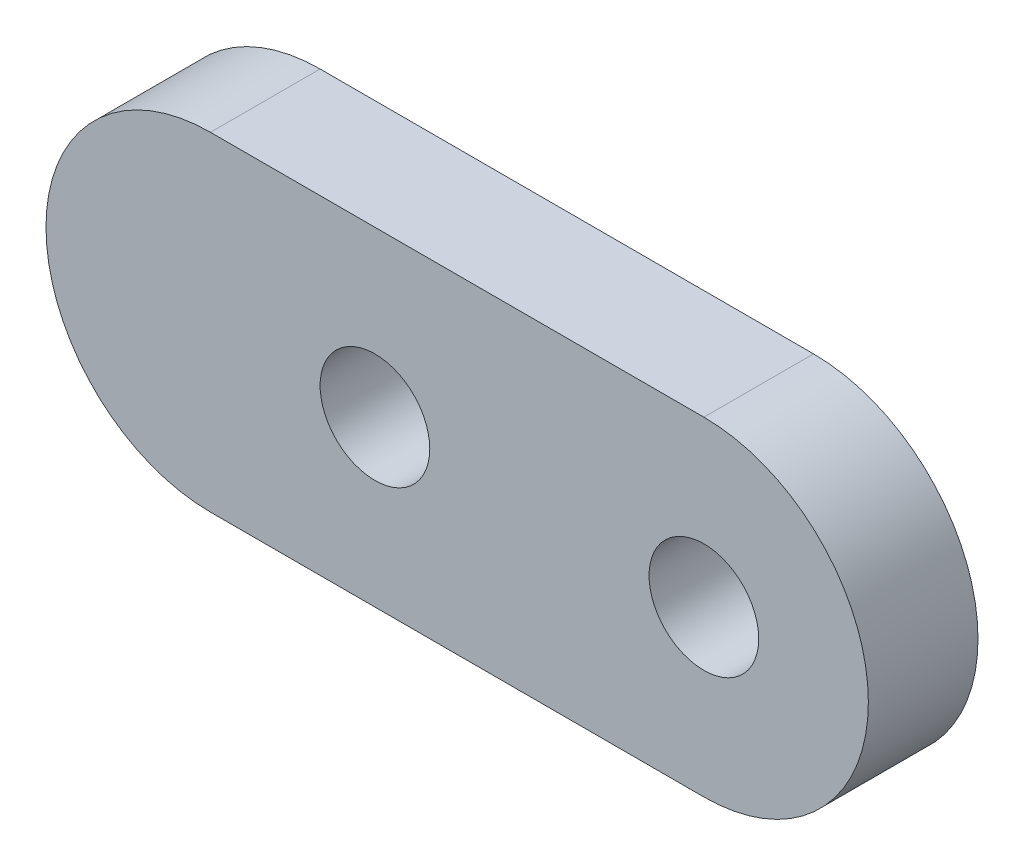
SolidWorks part; units mm, degrees
ref_plane "Alzado" through (0, 0, 0) normal (0, 0, 1) x (1, 0, 0)
ref_plane "Planta" through (0, 0, 0) normal (0, 1, 0) x (1, 0, 0)
ref_plane "Vista lateral" through (0, 0, 0) normal (1, 0, 0) x (0, 0, -1)
sketch "Model" plane through (0, 0, 0) normal (0, 0, 1) x (1, 0, 0)
  line L0 (-1487.8879, 378.5382) -> (-1501.3879, 378.5382)
  line L1 (-1487.8879, 369.5382) -> (-1501.3879, 369.5382)
  circle A0 centre (-1487.8879, 374.0382) radius 1.5
  circle A1 centre (-1496.8879, 374.0382) radius 1.5
  arc A2 (-1487.8879, 369.5382) -> (-1487.8879, 378.5382) centre (-1487.8879, 374.0382) ccw
  arc A3 (-1501.3879, 378.5382) -> (-1501.3879, 369.5382) centre (-1501.3879, 374.0382) ccw
extrude "Saliente-Extruir1" add sketch "Model" along normal blind 3
